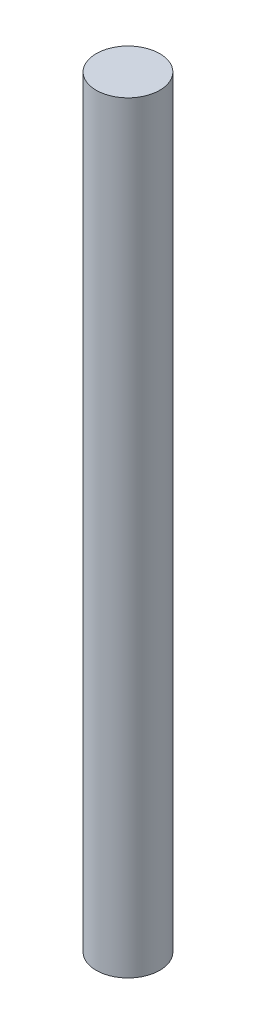
SolidWorks part; units mm, degrees
material "Alliage 1060"
ref_plane "Plan de face" through (0, 0, 0) normal (0, 0, 1) x (1, 0, 0)
ref_plane "Plan de dessus" through (0, 0, 0) normal (0, 1, 0) x (1, 0, 0)
ref_plane "Plan de droite" through (0, 0, 0) normal (1, 0, 0) x (0, 0, -1)
sketch "Esquisse1" plane through (0, 0, 0) normal (0, 1, 0) x (1, 0, 0)
  circle A0 centre (0, 0) radius 2.5
  dimension "D1" = 5
extrude "Boss.-Extru.1" add sketch "Esquisse1" along normal blind 60
